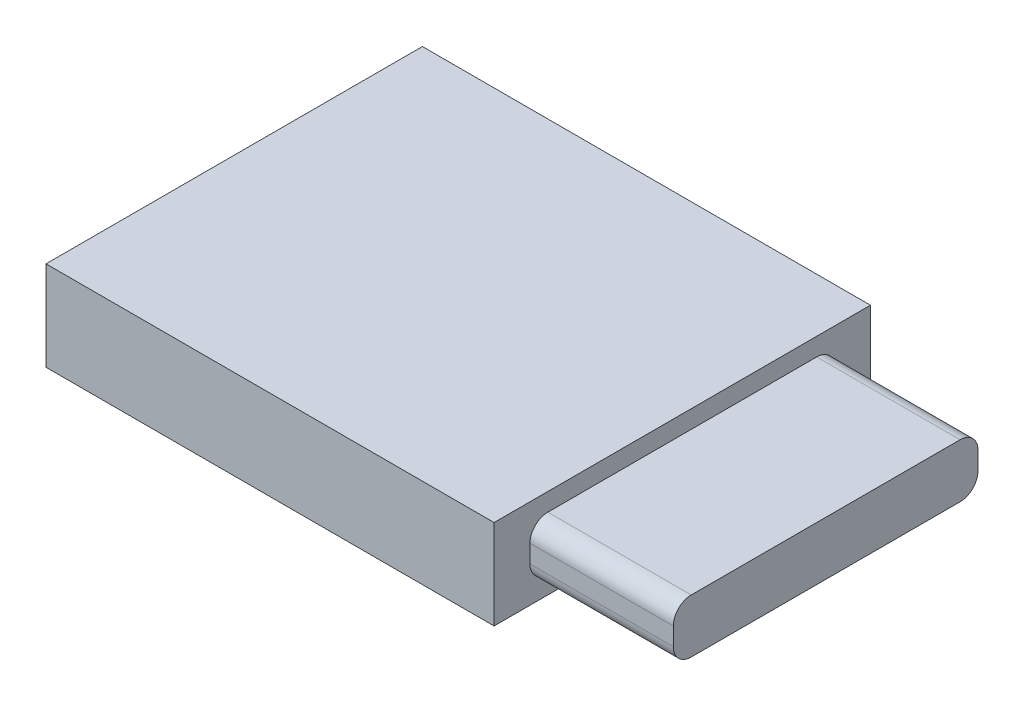
SolidWorks part; units mm, degrees
ref_plane "Front Plane" through (0, 0, 0) normal (0, 0, 1) x (1, 0, 0)
ref_plane "Top Plane" through (0, 0, 0) normal (0, 1, 0) x (1, 0, 0)
ref_plane "Right Plane" through (0, 0, 0) normal (1, 0, 0) x (0, 0, -1)
sketch "Sketch1" plane through (0, 0, 0) normal (0, 1, 0) x (1, 0, 0)
  line L1 (-12.5, -10.5) -> (12.5, -10.5)
  line L2 (-12.5, -10.5) -> (-12.5, 10.5)
  line L3 (-12.5, 10.5) -> (12.5, 10.5)
  line L4 (12.5, -10.5) -> (12.5, 10.5)
  line L5 (-12.5, -10.5) -> (12.5, 10.5) construction
  line L6 (-12.5, 10.5) -> (12.5, -10.5) construction
  point P0 (0, 0)
  dimension "D1" = 21
  dimension "D2" = 25
extrude "Boss-Extrude1" add sketch "Sketch1" along normal blind 5
sketch "Sketch2" plane through (12.5, 0, 0) normal (1, 0, 0) x (0, 0, -1)
  line L0 (-10.5, 0) -> (10.5, 5)
  line L2 (-7.5, 4) -> (7.5, 4)
  line L3 (-8.5, 3) -> (-8.5, 2)
  line L4 (-7.5, 1) -> (7.5, 1)
  line L5 (8.5, 3) -> (8.5, 2)
  line L6 (-8.5, 4) -> (8.5, 1) construction
  line L7 (-8.5, 1) -> (8.5, 4) construction
  arc A0 (8.5, 3) -> (7.5, 4) centre (7.5, 3) ccw
  arc A1 (7.5, 1) -> (8.5, 2) centre (7.5, 2) ccw
  arc A2 (-8.5, 2) -> (-7.5, 1) centre (-7.5, 2) ccw
  arc A3 (-7.5, 4) -> (-8.5, 3) centre (-7.5, 3) ccw
  point P4 (0, 2.5)
  dimension "D3" = 1
  dimension "D1" = 17
  dimension "D2" = 3
extrude "Boss-Extrude2" add sketch "Sketch2" along normal blind 8 contours L2 A3 L3 A2 L4 L0 | L4 A1 L5 A0 L2 L0
